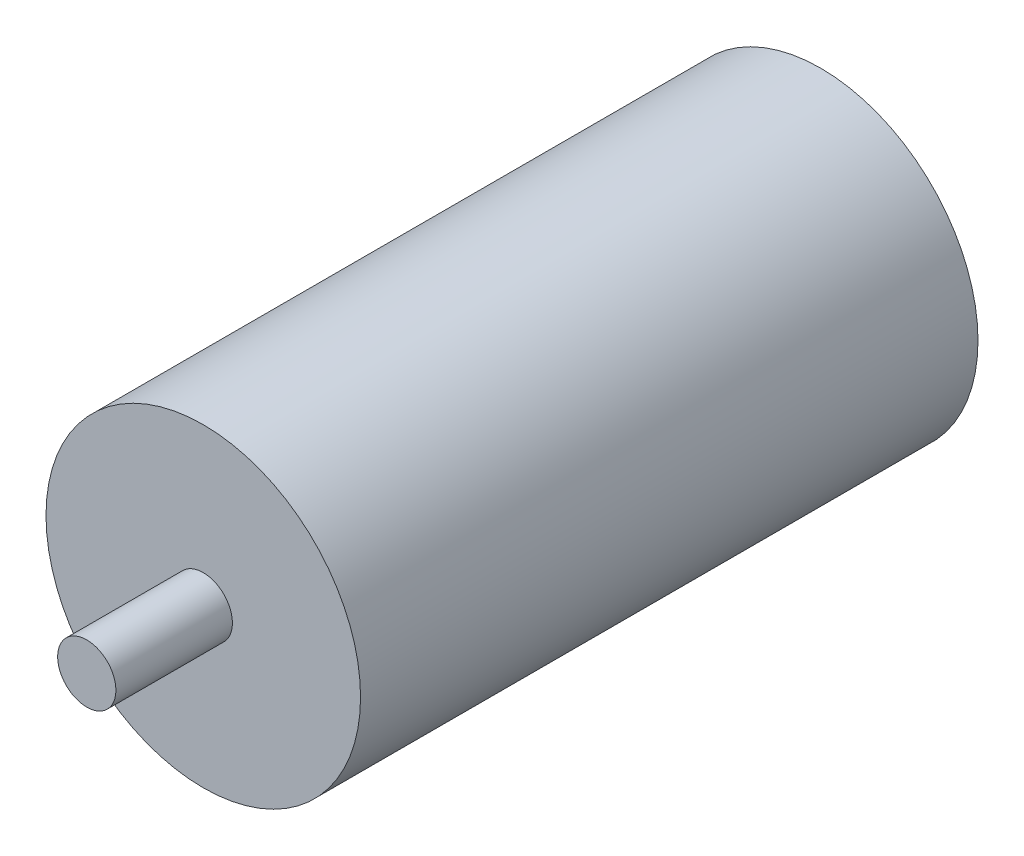
SolidWorks part; units mm, degrees
material "Titanium Ti-8Al-1Mo-1V"
ref_plane "Front Plane" through (0, 0, 0) normal (0, 0, 1) x (1, 0, 0)
ref_plane "Top Plane" through (0, 0, 0) normal (0, 1, 0) x (1, 0, 0)
ref_plane "Right Plane" through (0, 0, 0) normal (1, 0, 0) x (0, 0, -1)
sketch "Sketch1" plane through (0, 0, 0) normal (0, 0, 1) x (1, 0, 0)
  circle A0 centre (0, 0) radius 67.5
  dimension "D1" = 135
extrude "Boss-Extrude1" add sketch "Sketch1" along normal blind 265
sketch "Sketch2" plane through (0, 0, 265) normal (0, 0, 1) x (1, 0, 0)
  circle A0 centre (0, 0) radius 12.5
  dimension "D1" = 25
extrude "Boss-Extrude2" add sketch "Sketch2" along normal blind 50
